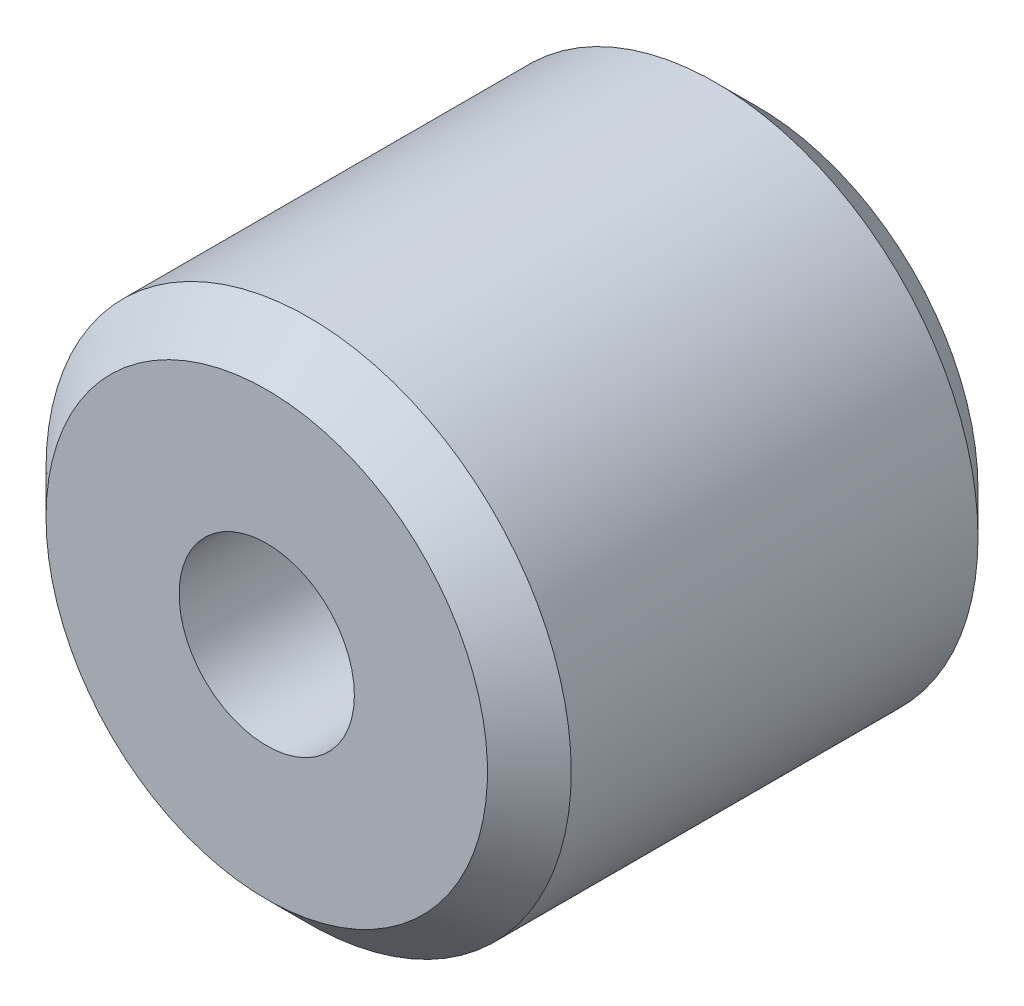
SolidWorks part; units mm, degrees
ref_plane "Front Plane" through (0, 0, 0) normal (0, 0, 1) x (1, 0, 0)
ref_plane "Top Plane" through (0, 0, 0) normal (0, 1, 0) x (1, 0, 0)
ref_plane "Right Plane" through (0, 0, 0) normal (1, 0, 0) x (0, 0, -1)
sketch "Sketch1" plane through (0, 0, 0) normal (0, 0, 1) x (1, 0, 0)
  circle A0 centre (0, 0) radius 4.765
  dimension "D1" = 9.53
extrude "Boss-Extrude1" add sketch "Sketch1" along normal mid plane 8.9
chamfer "Chamfer1" distance 0.76 angle 45 2 edges at (4.765, 0, -4.45) (4.765, 0, 4.45)
sketch "Sketch2" plane through (0, 0, 0) normal (0, 0, 1) x (1, 0, 0)
  circle A0 centre (0, 0) radius 1.59
  dimension "D1" = 3.18
extrude "Cut-Extrude1" cut sketch "Sketch2" against normal through all both and the other way through all
